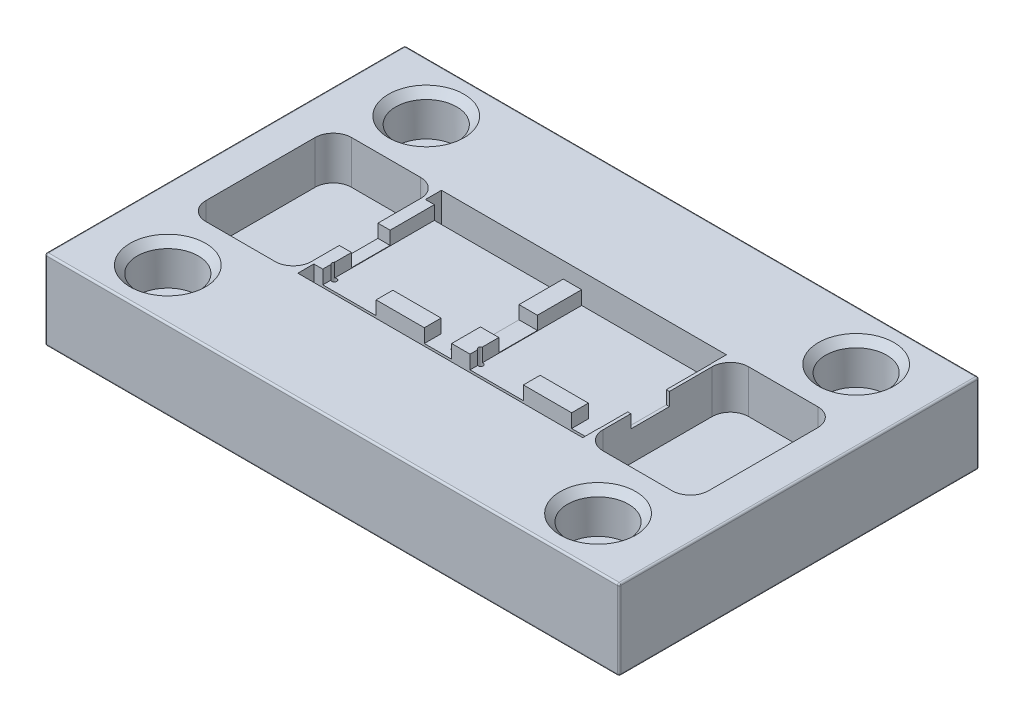
SolidWorks part; units mm, degrees
ref_plane "Front Plane" through (0, 0, 0) normal (0, 0, 1) x (1, 0, 0)
ref_plane "Top Plane" through (0, 0, 0) normal (0, 1, 0) x (1, 0, 0)
ref_plane "Right Plane" through (0, 0, 0) normal (1, 0, 0) x (0, 0, -1)
sketch "Sketch1" plane through (0, 0, 0) normal (0, 1, 0) x (1, 0, 0)
  line L1 (0, 0) -> (80.1116, 0)
  line L2 (0, 0) -> (0, 50.2158)
  line L3 (0, 50.2158) -> (80.1116, 50.2158)
  line L4 (80.1116, 0) -> (80.1116, 50.2158)
  dimension "D1" = 80.1116
  dimension "D2" = 50.2158
extrude "Boss-Extrude1" add sketch "Sketch1" along normal blind 11.176
hole_wizard "Hole1" positions "Sketch3" profile "Sketch2" legacy end condition through all
sketch "Sketch3" plane through (0, 11.176, 0) normal (0, 1, 0) x (1, 0, 0)
  line L0 (0, 0) -> (80.1116, 0) construction
  line L3 (0, 50.2158) -> (0, 0) construction
  line L5 (80.1116, 50.2158) -> (0, 50.2158) construction
  line L6 (80.1116, 0) -> (80.1116, 50.2158) construction
  point P0 (10.0457, 7.0993)
  point P2 (10.0584, 43.1419)
  point P4 (70.0532, 43.1292)
  point P6 (70.0532, 7.112)
  dimension "D1" = 7.0993
  dimension "D2" = 10.0457
  dimension "D3" = 10.0584
  dimension "D4" = 7.0739
  dimension "D5" = 10.0584
  dimension "D6" = 7.0866
  dimension "D7" = 7.112
  dimension "D8" = 10.0584
sketch "Sketch2" plane through (10.0457, 11.176, -7.0993) normal (1, 0, 0) x (0, 0, 1)
  line L0 (0, 0) -> (0, 11.176)
  line L1 (0, 11.176) -> (2.0955, 11.176)
  line L2 (2.0955, 11.176) -> (2.0955, 5.7912)
  line L3 (2.0955, 5.7912) -> (4.2545, 5.7912)
  line L4 (4.2545, 5.7912) -> (4.2545, 0)
  line L5 (4.2545, 0) -> (0, 0)
  line L6 (0, 110) -> (0, -10) construction
  dimension "Diameter" = 4.191
  dimension "Depth" = 11.176
  dimension "C-Bore Diameter" = 8.509
  dimension "C-Bore Depth" = 5.7912
chamfer "Chamfer1" distance 1.016 angle 45 4 edges at (10.0457, 11.176, -2.8448) (70.0532, 11.176, -2.8575) (70.0532, 11.176, -38.8747) (10.0584, 11.176, -38.8874)
fillet "Fillet1" radius 0.254 12 edges at (40.0558, 0, 0) (0, 0, -25.1079) (40.0558, 0, -50.2158) (80.1116, 0, -25.1079) (80.1116, 5.588, -50.2158) (80.1116, 5.588, 0) (0, 5.588, 0) (0, 5.588, -50.2158) (40.0558, 11.176, -50.2158) (80.1116, 11.176, -25.1079) (40.0558, 11.176, 0) (0, 11.176, -25.1079)
chamfer "Chamfer2" distance 0.762 angle 45 4 edges at (70.0532, 0, -41.0337) (70.0532, 0, -5.0165) (10.0584, 0, -41.0464) (10.0457, 0, -5.0038)
sketch "Sketch4" plane through (0, 0, 0) normal (0, -1, 0) x (1, 0, 0)
  line L0 (79.8576, -50.2158) -> (0.254, -50.2158) construction
  line L1 (20.0914, -15.1892) -> (59.8424, -15.1892)
  line L2 (20.0914, -15.1892) -> (20.0914, -17.4244)
  line L3 (20.0914, -17.4244) -> (59.8424, -17.4244)
  line L4 (59.8424, -15.1892) -> (59.8424, -17.4244)
  line L5 (20.0914, -32.9946) -> (59.8424, -32.9946)
  line L6 (20.0914, -32.9946) -> (20.0914, -35.2298)
  line L7 (20.0914, -35.2298) -> (59.8424, -35.2298)
  line L8 (59.8424, -32.9946) -> (59.8424, -35.2298)
  line L9 (0.254, -49.9618) -> (79.8576, -49.9618) construction
  line L11 (0, -49.9618) -> (0, -0.254) construction
  dimension "D1" = 39.751
  dimension "D2" = 39.751
  dimension "D3" = 2.2352
  dimension "D4" = 2.2352
  dimension "D5" = 14.986
  dimension "D6" = 32.5374
  dimension "D7" = 20.0914
  dimension "D8" = 20.0914
extrude "Cut-Extrude1" cut sketch "Sketch4" against normal through all
sketch "Sketch5" plane through (0, 0, 0) normal (0, -1, 0) x (1, 0, 0)
  line L0 (0, -49.9618) -> (0, -0.254) construction
  line L1 (79.8576, -50.2158) -> (0.254, -50.2158) construction
  circle A0 centre (21.5646, -18.8214) radius 1.2446
  circle A1 centre (38.3146, -18.8214) radius 1.2446
  dimension "D1" = 2.4892
  dimension "D2" = 21.5646
  dimension "D3" = 31.3944
  dimension "D5" = 16.75
  dimension "D4" = 2
extrude "Cut-Extrude2" cut sketch "Sketch5" against normal blind 4.2164
pattern_linear "LPattern1" count 2 spacing 20.4216 along (1, 0, 0) of "Cut-Extrude2"
hole_wizard "Ø1.0mm Dowel Hole1" positions "Sketch10" profile "Sketch11" hole size "Ø1.0" standard "ANSI Metric" end condition through all
sketch "Sketch10" plane through (0, 4.2164, 0) normal (0, -1, 0) x (-1, 0, 0)
  point P0 (-21.5646, 18.8214)
  point P3 (-38.3146, 18.8214)
  point P6 (-41.9862, 18.8214)
  point P9 (-58.7362, 18.8214)
sketch "Sketch11" plane through (21.5646, 4.2164, -18.8214) normal (1, 0, 0) x (0, 0, -1)
  line L0 (0, 0) -> (0, 6.9596)
  line L1 (0, 6.9596) -> (0.3429, 6.9596)
  line L2 (0.3429, 6.9596) -> (0.3429, 0)
  line L5 (0.3429, 0) -> (0, 0)
  line L11 (0, -6.35) -> (0, 107.95) construction
  dimension "Thru Hole Dia." = 0.6858
  dimension "Thru Hole Depth" = 6.9596
sketch "Sketch12" plane through (0, 11.176, 0) normal (0, 1, 0) x (1, 0, 0)
  line L0 (79.8576, 0) -> (0.254, 0) construction
  line L1 (4.9022, 15.0114) -> (19.6342, 15.0114)
  line L2 (4.9022, 15.0114) -> (4.9022, 35.3314)
  line L3 (4.9022, 35.3314) -> (19.6342, 35.3314)
  line L4 (19.6342, 15.0114) -> (19.6342, 35.3314)
  line L5 (0, 0.254) -> (0, 49.9618) construction
  line L7 (60.2996, 15.0114) -> (75.0316, 15.0114)
  line L8 (60.2996, 15.0114) -> (60.2996, 35.3314)
  line L9 (60.2996, 35.3314) -> (75.0316, 35.3314)
  line L10 (75.0316, 15.0114) -> (75.0316, 35.3314)
  dimension "D1" = 15.0114
  dimension "D2" = 4.9022
  dimension "D3" = 14.732
  dimension "D4" = 20.32
  dimension "D5" = 60.2996
  dimension "D6" = 15.0114
  dimension "D7" = 20.32
  dimension "D8" = 14.732
extrude "Cut-Extrude3" cut sketch "Sketch12" against normal blind 6.0198
fillet "Fillet2" radius 2.54 8 edges at (75.0316, 8.1661, -35.3314) (75.0316, 8.1661, -15.0114) (19.6342, 8.1661, -15.0114) (60.2996, 8.1661, -15.0114) (4.9022, 8.1661, -15.0114) (4.9022, 8.1661, -35.3314) (60.2996, 8.1661, -35.3314) (19.6342, 8.1661, -35.3314)
sketch "Sketch13" plane through (0, 11.176, 0) normal (0, 1, 0) x (1, 0, 0)
  line L0 (79.8576, 0) -> (0.254, 0) construction
  line L1 (28.7782, 19.7612) -> (35.5092, 19.7612)
  line L2 (21.336, 19.7612) -> (21.336, 32.9946)
  line L3 (21.336, 32.9946) -> (39.3192, 32.9946)
  line L4 (39.3192, 19.7612) -> (39.3192, 32.9946)
  line L5 (49.3268, 19.7612) -> (56.0578, 19.7612)
  line L6 (41.8846, 19.7612) -> (41.8846, 32.9946)
  line L7 (41.8846, 32.9946) -> (59.8678, 32.9946)
  line L8 (59.8678, 19.7612) -> (59.8678, 32.9946)
  line L9 (0, 0.254) -> (0, 49.9618) construction
  line L10 (59.8424, 32.9946) -> (20.0914, 32.9946) construction
  line L11 (20.0914, 17.4244) -> (59.8424, 17.4244) construction
  line L13 (21.336, 19.7612) -> (21.336, 17.4244)
  line L14 (21.336, 17.4244) -> (28.7782, 17.4244)
  line L15 (28.7782, 19.7612) -> (28.7782, 17.4244)
  line L17 (41.8846, 19.7612) -> (41.8846, 17.4244)
  line L18 (39.3192, 19.7612) -> (39.3192, 17.4244)
  line L19 (39.3192, 17.4244) -> (35.5092, 17.4244)
  line L20 (35.5092, 19.7612) -> (35.5092, 17.4244)
  line L21 (41.8846, 17.4244) -> (49.3268, 17.4244)
  line L22 (49.3268, 19.7612) -> (49.3268, 17.4244)
  line L24 (59.8678, 19.7612) -> (59.8678, 17.4244)
  line L25 (59.8678, 17.4244) -> (56.0578, 17.4244)
  line L26 (56.0578, 19.7612) -> (56.0578, 17.4244)
  dimension "D1" = 19.7612
  dimension "D2" = 19.7612
  dimension "D3" = 21.336
  dimension "D4" = 41.8846
  dimension "D5" = 17.9832
  dimension "D6" = 17.9832
  dimension "D7" = 0
  dimension "D8" = 0
  dimension "D9" = 7.4422
  dimension "D10" = 3.81
  dimension "D11" = 7.4422
  dimension "D12" = 3.81
extrude "Cut-Extrude4" cut sketch "Sketch13" against normal blind 1.905
sketch "Sketch14" plane through (60.2996, 0, 0) normal (1, 0, 0) x (0, 0, -1)
  line L0 (32.7914, 11.176) -> (17.5514, 11.176) construction
  line L1 (21.4376, 11.176) -> (26.8224, 11.176)
  line L2 (21.4376, 11.176) -> (21.4376, 9.3378)
  line L3 (21.4376, 9.3378) -> (26.8224, 9.3378)
  line L4 (26.8224, 11.176) -> (26.8224, 9.3378)
  line L6 (0.254, 10.922) -> (0.254, 0.254) construction
  dimension "D1" = 21.1836
  dimension "D2" = 5.3848
extrude "Cut-Extrude5" cut sketch "Sketch14" against normal up to surface (40.6654 mm away) up to face at (19.6342, 8.1661, -25.1714)
